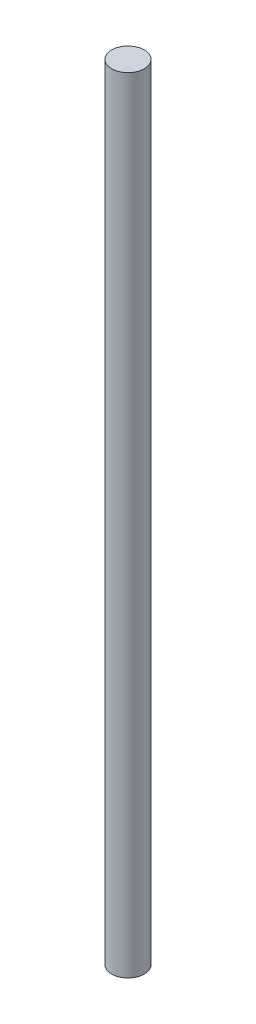
SolidWorks part; units mm, degrees
ref_plane "前视基准面" through (0, 0, 0) normal (0, 0, 1) x (1, 0, 0)
ref_plane "上视基准面" through (0, 0, 0) normal (0, 1, 0) x (1, 0, 0)
ref_plane "右视基准面" through (0, 0, 0) normal (1, 0, 0) x (0, 0, -1)
sketch "草图1" plane through (0, 0, 0) normal (0, 1, 0) x (1, 0, 0)
  circle A0 centre (0, 0) radius 5
  dimension "D1" = 10
extrude "凸台-拉伸1" add sketch "草图1" along normal blind 240
